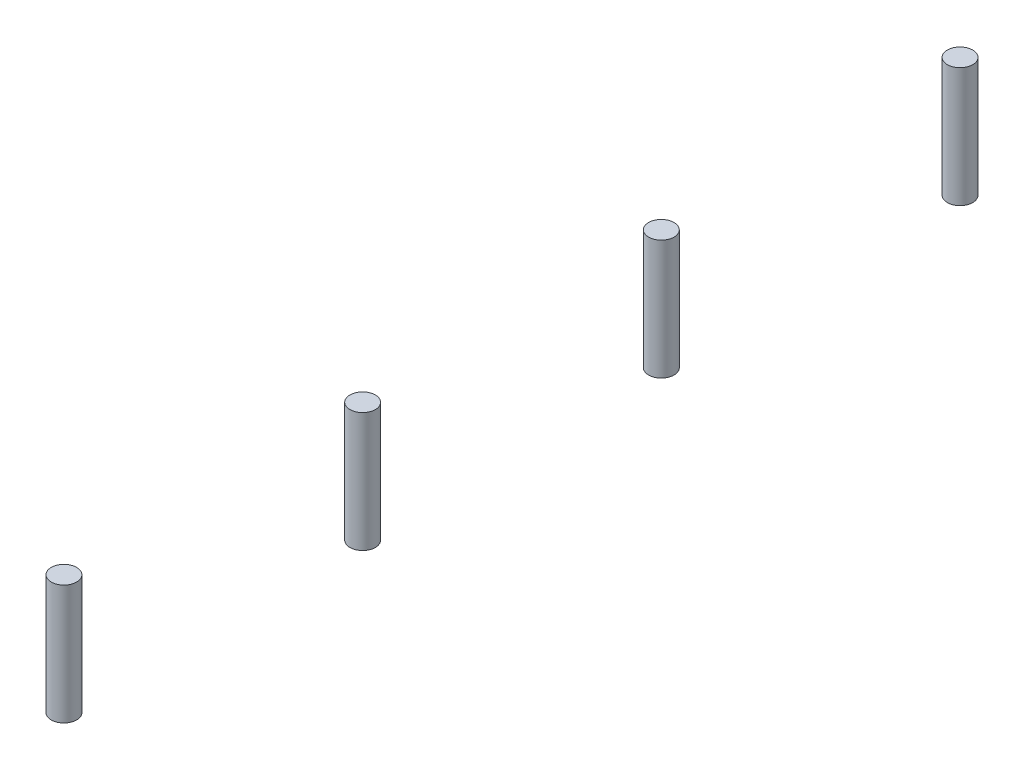
SolidWorks part; units mm, degrees
ref_plane "Front Plane" through (0, 0, 0) normal (0, 0, 1) x (1, 0, 0)
ref_plane "Top Plane" through (0, 0, 0) normal (0, 1, 0) x (1, 0, 0)
ref_plane "Right Plane" through (0, 0, 0) normal (1, 0, 0) x (0, 0, -1)
sketch "Sketch3" plane through (0, 0, 0) normal (0, 1, 0) x (1, 0, 0)
  circle A4 centre (-1, 5) radius 0.425
  circle A8 centre (-1, 15) radius 0.425
  circle A12 centre (-1, 25) radius 0.425
  circle A16 centre (-1, 35) radius 0.425
extrude "Boss-Extrude1" add sketch "Sketch3" along normal blind 4
